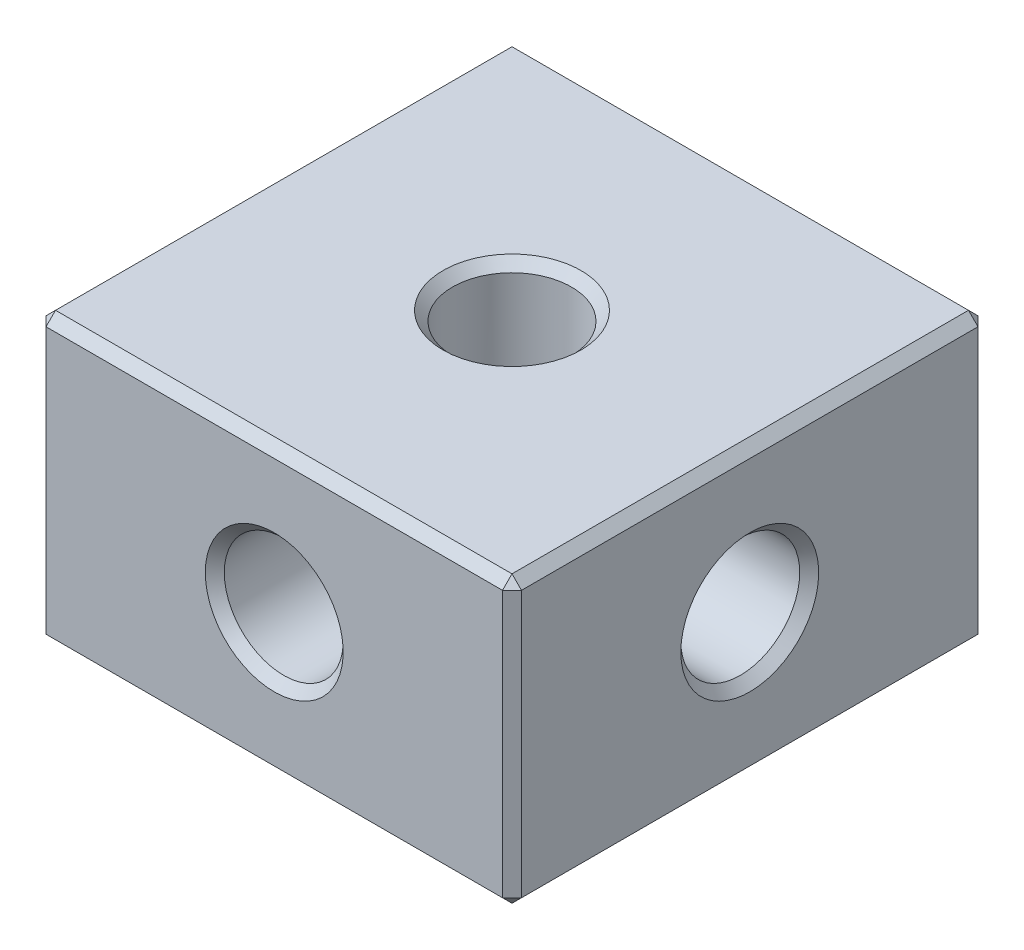
SolidWorks part; units mm, degrees
ref_plane "前视基准面" through (0, 0, 0) normal (0, 0, 1) x (1, 0, 0)
ref_plane "上视基准面" through (0, 0, 0) normal (0, 1, 0) x (1, 0, 0)
ref_plane "右视基准面" through (0, 0, 0) normal (1, 0, 0) x (0, 0, -1)
sketch "草图1" plane through (0, 0, 0) normal (0, 1, 0) x (1, 0, 0)
  line L1 (-5, 5) -> (5, 5)
  line L2 (-5, 5) -> (-5, -5)
  line L3 (-5, -5) -> (5, -5)
  line L4 (5, 5) -> (5, -5)
  line L5 (-5, 5) -> (5, -5) construction
  line L6 (-5, -5) -> (5, 5) construction
  point P0 (0, 0)
  dimension "D1" = 10
extrude "凸台-拉伸1" add sketch "草图1" along normal mid plane 6
hole_wizard "M3 螺纹孔1" positions "草图2" profile "草图3" tap size "M3" standard "GB" end condition through all
sketch "草图2" plane through (0, 0, 5) normal (0, 0, 1) x (1, 0, 0)
  point P0 (0, 0)
sketch "草图3" plane through (0, 0, 5) normal (1, 0, 0) x (0, -1, 0)
  line L0 (0, 0) -> (0, 10)
  line L1 (0, 10) -> (1.25, 10)
  line L2 (1.25, 10) -> (1.25, 0)
  line L5 (1.25, 0) -> (0, 0)
  line L11 (0, -6.35) -> (0, 107.95) construction
  dimension "通孔螺纹孔钻头直径" = 2.5
  dimension "通孔螺纹孔钻头深度" = 10
cosmetic thread "孔螺蚊线1" parameters "D2"=3
hole_wizard "M3 螺纹孔2" positions "草图4" profile "草图5" tap size "M3" standard "GB" end condition through all
sketch "草图4" plane through (0, 3, 0) normal (0, 1, 0) x (1, 0, 0)
  point P0 (0, 0)
sketch "草图5" plane through (0, 3, 0) normal (1, 0, 0) x (0, 0, 1)
  line L0 (0, 0) -> (0, 6)
  line L1 (0, 6) -> (1.25, 6)
  line L2 (1.25, 6) -> (1.25, 0)
  line L5 (1.25, 0) -> (0, 0)
  line L11 (0, -6.35) -> (0, 107.95) construction
  dimension "通孔螺纹孔钻头直径" = 2.5
  dimension "通孔螺纹孔钻头深度" = 6
cosmetic thread "孔螺蚊线2" parameters "D2"=3
hole_wizard "M3 螺纹孔3" positions "草图6" profile "草图7" tap size "M3" standard "GB" end condition through all
sketch "草图6" plane through (5, 0, 0) normal (1, 0, 0) x (0, 0, -1)
  point P0 (0, 0)
sketch "草图7" plane through (5, 0, 0) normal (0, 1, 0) x (0, 0, -1)
  line L0 (0, 0) -> (0, 10)
  line L1 (0, 10) -> (1.25, 10)
  line L2 (1.25, 10) -> (1.25, 0)
  line L5 (1.25, 0) -> (0, 0)
  line L11 (0, -6.35) -> (0, 107.95) construction
  dimension "通孔螺纹孔钻头直径" = 2.5
  dimension "通孔螺纹孔钻头深度" = 10
cosmetic thread "孔螺蚊线3" parameters "D2"=3
chamfer "倒角1" distance 0.2 angle 45 18 edges at (0, -3, 1.25) (-5, 0, -1.25) (1.25, 0, -5) (5, 0, -1.25) (1.25, 0, 5) (-5, -3, 0) (-5, 0, -5) (0, -3, -5) (5, 0, -5) (5, -3, 0) (-5, 0, 5) (0, -3, 5) (5, 0, 5) (0, 3, 5) (-5, 3, 0) (0, 3, -5) (5, 3, 0) (0, 3, 1.25)
